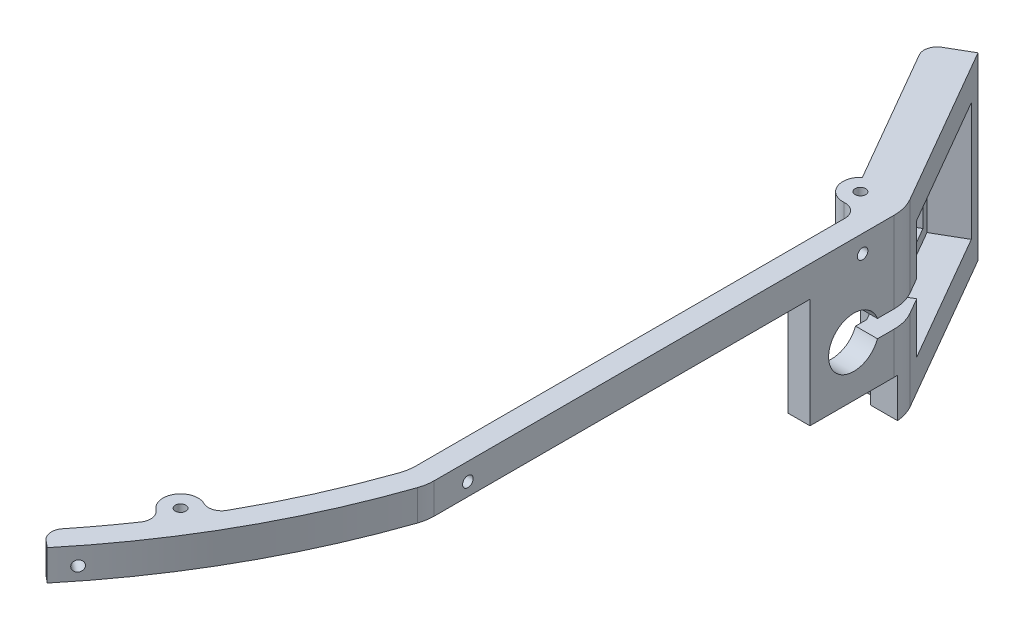
SolidWorks part; units mm, degrees
material "ABS"
ref_plane "Plan de face" through (0, 0, 0) normal (0, 0, 1) x (1, 0, 0)
ref_plane "Plan de dessus" through (0, 0, 0) normal (0, 1, 0) x (1, 0, 0)
ref_plane "Plan de droite" through (0, 0, 0) normal (1, 0, 0) x (0, 0, -1)
sketch "Esquisse1" plane through (0, 0, 0) normal (0, 1, 0) x (1, 0, 0)
  line L0 (163.5, -54.3149) -> (163.5, 54.8397)
  line L1 (163.5, 54.8397) -> (141, 93.8109)
  line L2 (158.5, -53.5) -> (158.5, 53.5)
  line L3 (158.5, 53.5) -> (136.6699, 91.3109)
  line L4 (165, -54.557) -> (165, 55.2417) construction
  line L5 (163.5, 54.8397) -> (103.2187, 159.25) construction
  line L6 (158.5, 53.5) -> (98.8886, 156.75) construction
  line L7 (141, 93.8109) -> (136.6699, 91.3109)
  line L8 (132.5985, -110) -> (128.7503, -106.8076)
  line L12 (0, 160) -> (104.5177, 160) construction
  line L13 (165, 55.2417) -> (104.5177, 160) construction
  arc A0 (132.5985, -110) -> (163.5, -54.3149) centre (0, 0) ccw
  arc A1 (128.7503, -106.8076) -> (158.5, -53.5) centre (0, 0) ccw
  arc A2 (111.9744, -130.9354) -> (163.5, -54.3149) centre (0, 0) ccw construction
  arc A3 (108.7248, -127.1355) -> (158.5, -53.5) centre (0, 0) ccw construction
  arc A5 (0, -145) -> (112.9493, -132.0754) centre (0, 355) ccw construction
  arc A6 (112.9493, -132.0754) -> (165, -54.557) centre (0, 0) ccw construction
  dimension "D1" = 1.5
  dimension "D2" = 5
  dimension "D3" = 45
  dimension "D4" = 110
extrude "Boss.-Extru.1" add sketch "Esquisse1" along normal blind 7
sketch "Esquisse2" plane through (0, 7, 0) normal (0, 1, 0) x (1, 0, 0)
  circle A0 centre (155, 53) radius 1.2
  circle A1 centre (155, 53) radius 4
  circle A2 centre (140, -87) radius 4
  circle A3 centre (140, -87) radius 1.2
  dimension "D1" = 155
  dimension "D2" = 53
  dimension "D3" = 2.4
  dimension "D4" = 8
  dimension "D5" = 140
  dimension "D6" = 87
extrude "Boss.-Extru.2" add sketch "Esquisse2" against normal up to surface (7 mm away) up to face at (148.5083, 0, 4.2462)
fillet "Congé1" radius 10 3 edges at (158.5, 3.5, 53.5) (163.5, 3.5, 54.3149) (163.5, 3.5, -54.8397)
fillet "Congé2" radius 3 5 edges at (128.7503, 3.5, 106.8076) (140.3809, 3.5, 90.9818) (143.7388, 3.5, 85.5783) (156.6976, 3.5, -56.6219) (158.5, 3.5, -51.0635)
sketch "Esquisse3" plane through (0, 7, 0) normal (0, 1, 0) x (1, 0, 0)
  line L0 (141, 93.8109) -> (115.6418, 79.1703)
  line L1 (141, 93.8109) -> (158.5, 63.5)
  line L2 (115.6418, 79.1703) -> (129.8853, 54.5)
  line L3 (158.5, 54.5) -> (129.8853, 54.5)
  line L4 (141, 93.8109) -> (136.6699, 91.3109) construction
  line L5 (158.5, 46.0179) -> (158.5, -51.8318) construction
  line L6 (158.5, 63.5) -> (158.5, 54.5)
  line L7 (162.1603, 57.1603) -> (141, 93.8109) construction
  line L8 (101.9115, 108.9519) -> (120.9641, 119.9519)
  line L9 (101.9115, 108.9519) -> (116.4115, 83.8372)
  line L10 (120.9641, 119.9519) -> (135.4641, 94.8372)
  line L11 (116.4115, 83.8372) -> (123.9893, 88.2122)
  line L12 (123.9893, 88.2122) -> (128.4685, 80.4539)
  line L13 (127.8864, 90.4622) -> (135.4641, 94.8372)
  line L14 (127.8864, 90.4622) -> (132.3656, 82.7039)
  line L16 (111.4378, 114.4519) -> (133.0628, 76.9963) construction
  circle A0 centre (155, 53) radius 1.2 construction
  circle A1 centre (155, 53) radius 1.2 construction
  arc A2 (128.4685, 80.4539) -> (132.3656, 82.7039) centre (133.0628, 76.9963) ccw
  dimension "D1" = 22
  dimension "D3" = 11.5
  dimension "D10" = 22.4963
  dimension "D2" = 29
  dimension "D4" = 7
  dimension "D5" = 75
  dimension "D6" = 32.6567
  dimension "D7" = 3
  dimension "D8" = 4.5
  dimension "D9" = 14.25
  dimension "D11" = 1.5
sketch "Esquisse4" plane through (0, 7, 0) normal (0, 1, 0) x (1, 0, 0)
  line L0 (162.1603, 57.1603) -> (141, 93.8109) construction
  line L1 (163.5, -52.6725) -> (163.5, 52.1603) construction
  line L2 (158.5, 46.0179) -> (158.5, -51.8318) construction
  line L3 (141, 93.8109) -> (136.6699, 91.3109) construction
  line L5 (162.1603, 57.1603) -> (141, 93.8109)
  line L7 (163.5, 33) -> (163.5, 52.1603)
  line L8 (158.5, 50.9378) -> (158.5, 33)
  line L9 (141, 93.8109) -> (133.2058, 89.3109)
  line L10 (133.2058, 89.3109) -> (153.0152, 55)
  line L11 (158.5, 33) -> (163.5, 33)
  line L12 (156.7321, 54) -> (158.5, 50.9378)
  line L13 (155, 55) -> (153.0152, 55)
  arc A0 (163.5, 52.1603) -> (162.1603, 57.1603) centre (153.5, 52.1603) ccw construction
  arc A1 (163.5, 52.1603) -> (162.1603, 57.1603) centre (153.5, 52.1603) ccw
  arc A2 (156.7321, 54) -> (155, 55) centre (155, 53) ccw
  circle A3 centre (155, 53) radius 1.2 construction
  dimension "D3" = 20
  dimension "D4" = 4
  dimension "D2" = 9
extrude "Boss.-Extru.3" add sketch "Esquisse4" against normal blind 41
sketch "Esquisse5" plane through (146.3713, 0, -84.5075) normal (0.866, 0, -0.5) x (-0.5, 0, -0.866)
  line L0 (4.0824, -13.5) -> (10.7426, -13.5) construction
  line L1 (-24.9176, -2.5) -> (4.0824, -2.5)
  line L2 (-24.9176, -2.5) -> (-24.9176, -24.5)
  line L3 (-24.9176, -24.5) -> (4.0824, -24.5)
  line L4 (4.0824, -2.5) -> (4.0824, -24.5)
  line L5 (10.7426, 7) -> (10.7426, -34) construction
  line L6 (-10.4176, -2.5) -> (-10.4176, 7) construction
  line L7 (-31.5779, 7) -> (10.7426, 7) construction
  dimension "D1" = 29
  dimension "D2" = 22
extrude "Enlèv. mat.-Extru.1" cut sketch "Esquisse5" against normal through all
sketch "Esquisse7" plane through (146.3713, 0, -84.5075) normal (0.866, 0, -0.5) x (-0.5, 0, -0.866)
  line L0 (-10.4176, 0) -> (-10.4176, -2.5) construction
  line L1 (-27.4176, 0) -> (6.5824, 0)
  line L2 (-27.4176, 0) -> (-27.4176, -27)
  line L3 (-27.4176, -27) -> (6.5824, -27)
  line L4 (6.5824, 0) -> (6.5824, -27)
  line L5 (4.0824, -2.5) -> (-24.9176, -2.5) construction
  line L7 (4.0824, -24.5) -> (4.0824, -2.5) construction
  line L8 (4.0824, -13.5) -> (6.5824, -13.5) construction
  dimension "D1" = 27
  dimension "D2" = 34
extrude "Enlèv. mat.-Extru.2" cut sketch "Esquisse7" against normal offset from surface (7.4 mm away) 1.6 up to face at (143.7859, -13.5, -70.9856)
sketch "Esquisse8" plane through (0, 7, 0) normal (0, 1, 0) x (1, 0, 0)
  line L0 (163.5, -52.6725) -> (163.5, 52.1603) construction
  line L1 (0, 0) -> (163.5, 0)
  line L2 (0, 0) -> (0, 53)
  line L3 (0, 53) -> (163.5, 53)
  line L4 (163.5, 0) -> (163.5, 53)
  point P7 (155, 53)
extrude "Enlèv. mat.-Extru.3" cut sketch "Esquisse8" against normal through all from offset 32 offset against normal yes
sketch "Esquisse9" plane through (163.5, 0, 0) normal (1, 0, 0) x (0, 0, -1)
  line L0 (60.7631, 0) -> (60.7631, -27) construction
  line L1 (60.7631, -11.5) -> (48.391, -11.5)
  line L2 (60.7631, -11.5) -> (60.7631, -15.5)
  line L3 (60.7631, -15.5) -> (48.391, -15.5)
  line L4 (48.391, -11.5) -> (48.391, -15.5) construction
  arc A0 (48.391, -11.5) -> (48.391, -15.5) centre (43, -13.5) ccw
  point P4 (60.7631, -13.5)
  dimension "D1" = 4
  dimension "D2" = 11.5
  dimension "D3" = 43
extrude "Enlèv. mat.-Extru.4" cut sketch "Esquisse9" against normal through all
fillet "Congé3" radius 3 1 edges at (133.2058, -13.5, -89.3109)
hole_wizard "Diamètre du perçage Ø2.4 (2.4)1" positions "Esquisse3D1" profile "Esquisse10" hole size "Ø2.4" standard "ISO" end condition through all
sketch3d "Esquisse3D1"
  line L0 (163.5, 7, 52.6725) -> (163.5, 7, -52.1603) construction
  line L1 (132.5985, 7, 110) -> (132.5985, 0, 110) construction
  point P0 (135.7347, 3, 106.1059)
  point P2 (163.5, 3, -45)
  point P4 (163.5, 3, 45)
  dimension "D1" = 4
  dimension "D2" = 4
  dimension "D3" = 4
  dimension "D4" = 5
  dimension "D5" = 45
  dimension "D6" = 45
sketch "Esquisse10" plane through (135.7347, 3, 106.1059) normal (0, 1, 0) x (0.6159, 0, -0.7878)
  line L0 (0, 0) -> (0, 127.6771)
  line L1 (0, 127.6771) -> (1.2, 127.6771)
  line L2 (1.2, 127.6771) -> (1.2, 0)
  line L5 (1.2, 0) -> (0, 0)
  line L11 (0, -6.35) -> (0, 107.95) construction
  dimension "Diamètre du perçage jusqu'au prochain" = 2.4
  dimension "Profondeur du perçage jusqu'au prochain" = 127.6771
